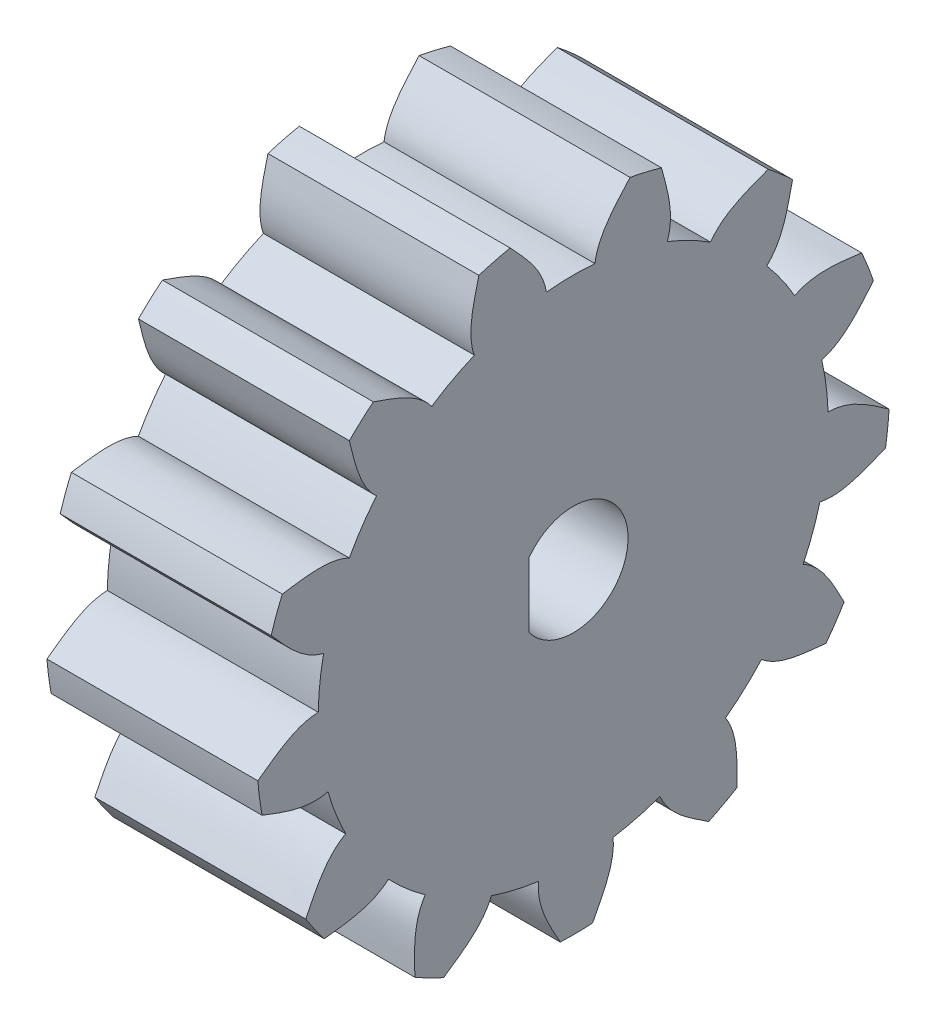
SolidWorks part; units mm, degrees
ref_plane "Front Plane" through (0, 0, 0) normal (1, 0, 0) x (0, 1, 0)
ref_plane "Top Plane" through (0, 0, 0) normal (0, 0, 1) x (0, 1, 0)
ref_plane "Right Plane" through (0, 0, 0) normal (0, 1, 0) x (-1, 0, 0)
sketch "Sketch1" plane through (0, 0, 0) normal (1, 0, 0) x (0, 1, 0)
  line L0 (0, 0) -> (0, 21.1652) construction
  line L1 (-11.5679, 13) -> (11.5679, 13) construction
  line L2 (-12.5523, 8.4313) -> (12.5523, 17.5687) construction
  line L3 (0, 0) -> (-4.1781, 11.4793) construction
  line L4 (-8.0315, 9.2047) -> (-1.2905, 15.0864) construction
  line L5 (-3.2255, 11.7825) -> (0.0985, 12.6924) construction
  circle A0 centre (0, 0) radius 13
  circle A1 centre (0, 0) radius 12.216 construction
  arc A2 (-4.1781, 11.4793) -> (-8.0315, 9.2047) centre (0, 0) ccw
  arc A3 (-4.1781, 11.4793) -> (-3.2255, 11.7825) centre (0, 0) cw
  point P7 (0, 13)
  point P10 (0, 13)
  dimension "D1" = 26
  dimension "D2" = 20
  dimension "D3" = 4.4463
  dimension "D5" = 8.9463
  dimension "D7" = 3.4463
  dimension "D4" = 4.5
  dimension "D6" = 1
sketch "Sketch2" plane through (0, 0, 0) normal (1, 0, 0) x (0, 1, 0)
  line L0 (0, 0) -> (0, 21.1652) construction
  line L1 (-5.9224, 11.2852) -> (2.7998, 12.4335) construction
  line L2 (0, 0) -> (-2.6319, 19.9912) construction
  circle A0 centre (0, 0) radius 12.0909
  circle A2 centre (0, 0) radius 15
  spline S0 degree 3 poles (-1.196, 14.9522) (-0.7741, 14.3593) (-0.196, 13.6226) (0.1208, 12.6425) (0.1752, 12.3366) (0.1856, 12.1314) (0.1866, 12.0894) knots 0.053107 0.053107 0.053107 0.053107 0.752323 0.851359 1 1.037972 1.037972 1.037972 1.037972
  spline S1 degree 3 poles (-2.7147, 14.7523) (-2.9688, 14.0704) (-3.3365, 13.2092) (-3.3888, 12.1805) (-3.3622, 11.8709) (-3.3191, 11.67) (-3.3092, 11.6292) knots 0.053107 0.053107 0.053107 0.053107 0.752323 0.851359 1 1.037972 1.037972 1.037972 1.037972
  point P24 (-1.5613, 11.8593)
  dimension "D1" = 30
  dimension "D2" = 7.5
sketch "Sketch3" plane through (0, 0, 0) normal (1, 0, 0) x (0, 1, 0)
  circle A0 centre (0, 0) radius 12.0909 construction
  circle A1 centre (0, 0) radius 12.0909
extrude "Boss-Extrude1" add sketch "Sketch3" along normal blind 10
sketch "Sketch4" plane through (0, 0, 0) normal (1, 0, 0) x (0, 1, 0)
  circle A0 centre (0, 0) radius 15 construction
  circle A1 centre (0, 0) radius 12.0909 construction
  arc A2 (-1.196, 14.9522) -> (-2.7147, 14.7523) centre (0, 0) ccw
  arc A3 (0.1866, 12.0894) -> (-3.3092, 11.6292) centre (0, 0) ccw
  spline S0 degree 3 poles (1997.186, 93.2583) (-2028.7706, -56.8661) (2024.1694, 124.1461) (-1990.3497, -179.0942) knots -12.650442 -12.650442 -12.650442 -12.650442 13.103997 13.103997 13.103997 13.103997 only from (-1.196, 14.9522) to (0.1866, 12.0894) construction
  spline S1 degree 3 poles (-1953.2706, -426.8292) (1974.3599, 470.156) (-1987.3288, -403.9777) (1968.8832, 342.1487) knots -12.650442 -12.650442 -12.650442 -12.650442 13.103997 13.103997 13.103997 13.103997 only from (-2.7147, 14.7523) to (-3.3092, 11.6292) construction
  spline S2 degree 3 poles (-1.196, 14.9522) (-0.6017, 14.1171) (0.1601, 13.178) (0.1866, 12.0894) knots 0.053107 0.053107 0.053107 0.053107 1.037972 1.037972 1.037972 1.037972
  spline S3 degree 3 poles (-2.7147, 14.7523) (-3.0725, 13.7918) (-3.5654, 12.6875) (-3.3092, 11.6292) knots 0.053107 0.053107 0.053107 0.053107 1.037972 1.037972 1.037972 1.037972
extrude "Boss-Extrude2" add sketch "Sketch4" along normal up to surface (10 mm away) up to face at (10, 0, -12.0909)
pattern_circular "CirPattern1" count 13 over 360 about axis through (10, 0, 0) along (1, 0, 0) of "Boss-Extrude2"
sketch "Sketch5" plane through (10, 0, 0) normal (1, 0, 0) x (0, 1, 0)
  line L0 (-1.5, 2) -> (1.5, 2) construction
  line L1 (-1.533, 2.1) -> (1.533, 2.1)
  arc A0 (-1.5, 2) -> (1.5, 2) centre (0, 0) ccw construction
  arc A2 (-1.533, 2.1) -> (1.533, 2.1) centre (0, 0) ccw
  point P7 (0, 2)
  dimension "D1" = 5
  dimension "D2" = 2
  dimension "D3" = 0.1
extrude "Cut-Extrude1" cut sketch "Sketch5" against normal through all
equation "\"D5@Sketch1\"=\"D3@Sketch1\"+\"D4@Sketch1\""
equation "\"D7@Sketch1\"=\"D3@Sketch1\"-\"D6@Sketch1\""
equation "\"D2@Sketch2\"=360/12/4"
